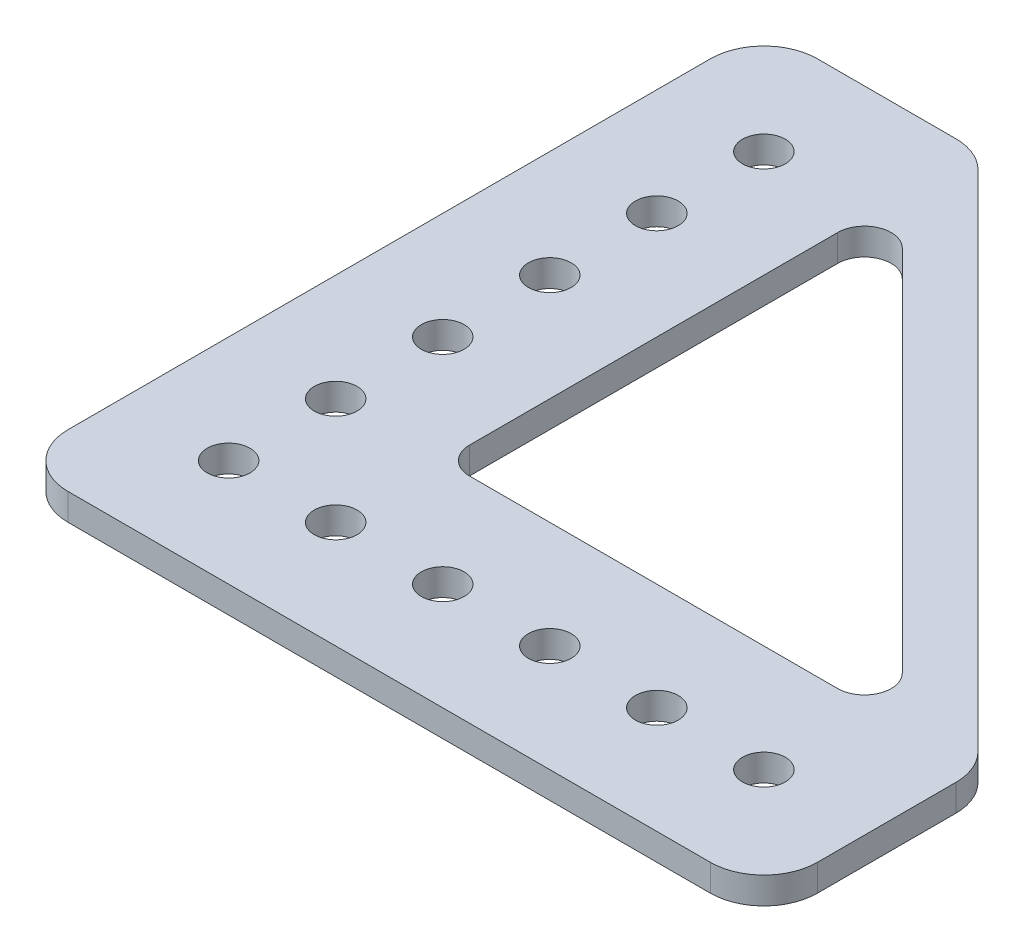
SolidWorks part; units mm, degrees
ref_plane "Front Plane" through (0, 0, 0) normal (0, 0, 1) x (1, 0, 0)
ref_plane "Top Plane" through (0, 0, 0) normal (0, 1, 0) x (1, 0, 0)
ref_plane "Right Plane" through (0, 0, 0) normal (1, 0, 0) x (0, 0, -1)
sketch "Sketch1" plane through (0, 0, 0) normal (0, 1, 0) x (1, 0, 0)
  line L0 (12.7, 88.9) -> (12.7, 0) construction
  line L2 (0, 0) -> (0, 88.9)
  line L3 (0, 88.9) -> (25.4, 88.9)
  line L4 (25.4, 25.4) -> (25.4, 79.9197)
  line L5 (0, 0) -> (88.9, 0)
  line L7 (25.4, 25.4) -> (79.9197, 25.4)
  line L8 (88.9, 0) -> (88.9, 25.4)
  line L9 (88.9, 12.7) -> (0, 12.7) construction
  line L10 (25.4, 88.9) -> (88.9, 25.4)
  line L11 (25.4, 79.9197) -> (79.9197, 25.4)
  line L12 (12.7, 12.7) -> (25.4, 12.7) construction
  line L13 (12.7, 12.7) -> (12.7, 25.4) construction
  circle A0 centre (12.7, 12.7) radius 2.54
  circle A1 centre (25.4, 12.7) radius 2.54
  circle A2 centre (38.1, 12.7) radius 2.54
  circle A3 centre (50.8, 12.7) radius 2.54
  circle A4 centre (63.5, 12.7) radius 2.54
  circle A5 centre (76.2, 12.7) radius 2.54
  circle A6 centre (12.7, 25.4) radius 2.54
  circle A7 centre (12.7, 38.1) radius 2.54
  circle A8 centre (12.7, 50.8) radius 2.54
  circle A9 centre (12.7, 63.5) radius 2.54
  circle A10 centre (12.7, 76.2) radius 2.54
  dimension "D6" = 5.08
  dimension "D1" = 88.9
  dimension "D2" = 88.9
  dimension "D3" = 25.4
  dimension "D4" = 25.4
  dimension "D8" = 12.7
  dimension "D10" = 12.7
  dimension "D7" = 6
  dimension "D9" = 6
extrude "Boss-Extrude1" add sketch "Sketch1" along normal blind 3.175
fillet "Fillet1" radius 6.35 5 edges at (0, 1.5875, 0) (88.9, 1.5875, 0) (88.9, 1.5875, -25.4) (25.4, 1.5875, -88.9) (0, 1.5875, -88.9)
fillet "Fillet2" radius 3.175 3 edges at (25.4, 1.5875, -25.4) (79.9197, 1.5875, -25.4) (25.4, 1.5875, -79.9197)
sketch "Sketch2" plane through (0, 0, 0) normal (0, -1, 0) x (1, 0, 0)
  line L0 (-983.9668, 0) -> (49016.0332, 0) construction
  line L2 (0, -1041.9981) -> (0, 48958.0019) construction
  line L4 (6.35, 0) -> (82.55, 0) construction
  line L5 (0, -82.55) -> (0, -6.35) construction
  point P3 (0, 0)
